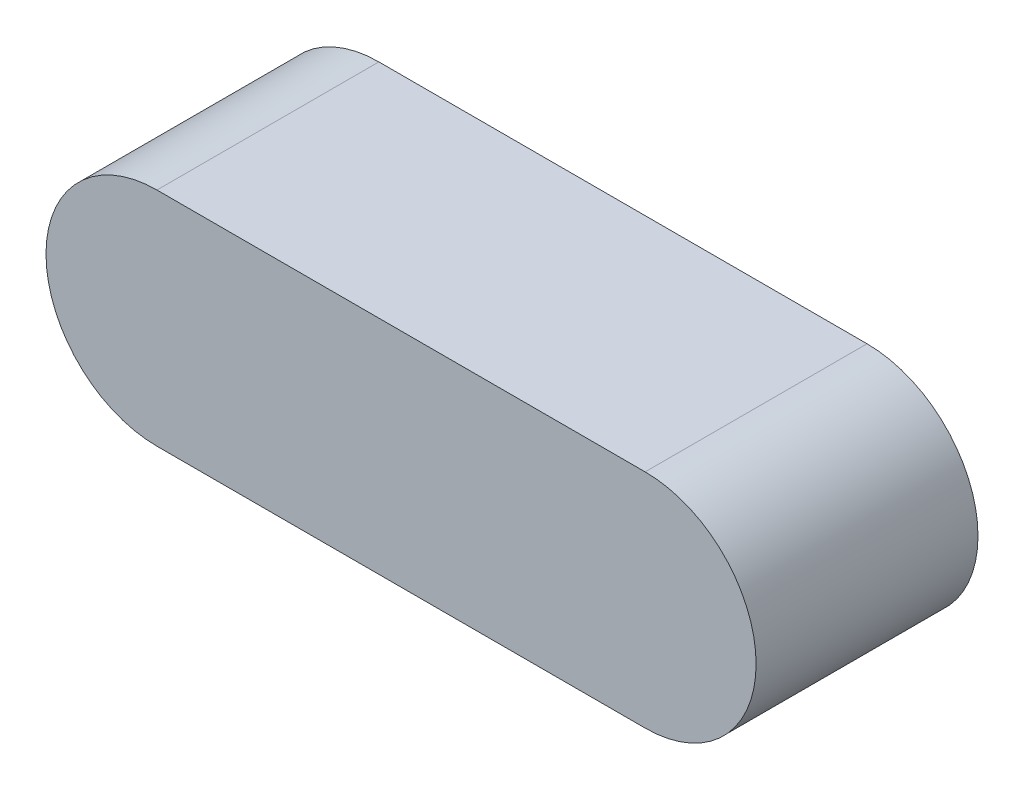
SolidWorks part; units mm, degrees
ref_plane "前视基准面" through (0, 0, 0) normal (0, 0, 1) x (1, 0, 0)
ref_plane "上视基准面" through (0, 0, 0) normal (0, 1, 0) x (1, 0, 0)
ref_plane "右视基准面" through (0, 0, 0) normal (1, 0, 0) x (0, 0, -1)
sketch "草图1" plane through (0, 0, 0) normal (0, 0, 1) x (1, 0, 0)
  line L0 (0, 0) -> (11, 0) construction
  line L1 (0, 2.5) -> (11, 2.5)
  line L2 (0, -2.5) -> (11, -2.5)
  arc A0 (0, 2.5) -> (0, -2.5) centre (0, 0) ccw
  arc A1 (11, -2.5) -> (11, 2.5) centre (11, 0) ccw
  point P3 (5.5, 0)
  dimension "D1" = 2.5
  dimension "D2" = 11
extrude "凸台-拉伸1" add sketch "草图1" along normal blind 5
